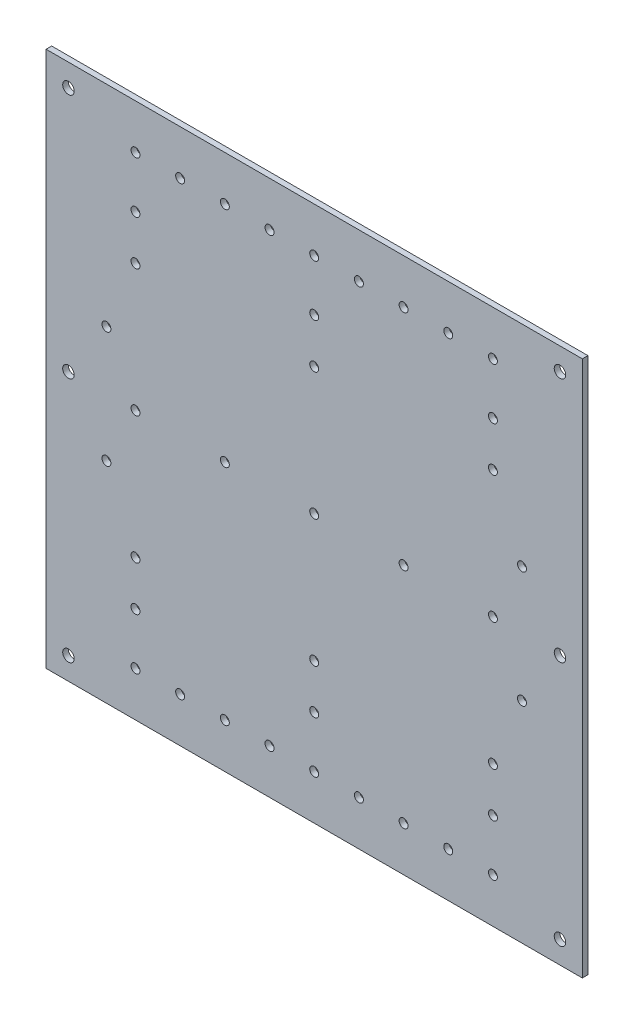
SolidWorks part; units mm, degrees
ref_plane "Front Plane" through (0, 0, 0) normal (0, 0, 1) x (1, 0, 0)
ref_plane "Top Plane" through (0, 0, 0) normal (0, 1, 0) x (1, 0, 0)
ref_plane "Right Plane" through (0, 0, 0) normal (1, 0, 0) x (0, 0, -1)
sketch "Sketch1" plane through (0, 0, 0) normal (0, 0, 1) x (1, 0, 0)
  line L0 (-152.4, 127) -> (-76.2, 127) construction
  line L1 (-152.4, 152.4) -> (152.4, 152.4)
  line L2 (-152.4, 152.4) -> (-152.4, -152.4)
  line L3 (-152.4, -152.4) -> (152.4, -152.4)
  line L4 (152.4, 152.4) -> (152.4, -152.4)
  line L5 (-76.2, 127) -> (-25.4, 127) construction
  line L6 (-25.4, 127) -> (25.4, 127) construction
  line L7 (25.4, 127) -> (76.2, 127) construction
  line L8 (76.2, 127) -> (152.4, 127) construction
  line L9 (-152.4, 0) -> (152.4, 0) construction
  line L10 (0, 152.4) -> (0, -152.4) construction
  line L11 (-118.11, 152.4) -> (-118.11, -152.4) construction
  line L12 (-152.4, -127) -> (152.4, -127) construction
  line L13 (127, 152.4) -> (127, -152.4) construction
  line L14 (-50.8, 152.4) -> (-50.8, -152.4) construction
  line L15 (50.8, 152.4) -> (50.8, -152.4) construction
  line L16 (-101.6, 152.4) -> (-101.6, -152.4) construction
  line L17 (-95.25, 66.04) -> (-57.15, 66.04) construction
  line L18 (-95.25, 66.04) -> (-95.25, -66.04) construction
  line L19 (-95.25, -66.04) -> (-57.15, -66.04) construction
  line L20 (-57.15, 66.04) -> (-57.15, -66.04) construction
  line L21 (-44.45, 66.04) -> (-6.35, 66.04) construction
  line L22 (-44.45, 66.04) -> (-44.45, -66.04) construction
  line L23 (-44.45, -66.04) -> (-6.35, -66.04) construction
  line L24 (-6.35, 66.04) -> (-6.35, -66.04) construction
  line L25 (6.35, 66.04) -> (44.45, 66.04) construction
  line L26 (6.35, 66.04) -> (6.35, -66.04) construction
  line L27 (6.35, -66.04) -> (44.45, -66.04) construction
  line L28 (44.45, 66.04) -> (44.45, -66.04) construction
  line L29 (57.15, 66.04) -> (95.25, 66.04) construction
  line L30 (57.15, 66.04) -> (57.15, -66.04) construction
  line L31 (57.15, -66.04) -> (95.25, -66.04) construction
  line L32 (95.25, 66.04) -> (95.25, -66.04) construction
  line L33 (101.6, 152.4) -> (101.6, -152.4) construction
  line L34 (-152.4, 120.65) -> (152.4, 120.65) construction
  line L35 (-101.6, 39.7057) -> (-95.25, 39.7057) construction
  line L36 (-57.15, 39.7057) -> (-50.8, 39.7057) construction
  line L37 (-76.2, 66.04) -> (-76.2, 0) construction
  line L38 (-76.2, 0) -> (-76.2, -66.04) construction
  line L39 (-152.4, 72.39) -> (152.4, 72.39) construction
  line L40 (-152.4, -72.39) -> (152.4, -72.39) construction
  line L41 (-76.2, 66.04) -> (-76.2, 72.39) construction
  line L42 (-95.25, -66.04) -> (-95.25, -72.39) construction
  line L43 (95.25, 39.7057) -> (101.6, 39.7057) construction
  line L44 (-95.25, 111.76) -> (-57.15, 111.76) construction
  line L45 (-57.15, 111.76) -> (-57.15, 118.4779) construction
  line L46 (-94.0266, 120.65) -> (-78.1749, 130.2582) construction
  line L47 (-95.25, 111.76) -> (-95.25, 118.4779) construction
  line L48 (-58.3734, 120.65) -> (-74.2251, 130.2582) construction
  line L49 (-107.3169, 130.81) -> (-83.1894, 130.81) construction
  line L50 (-6.35, 111.76) -> (-6.35, 118.4779) construction
  line L51 (-7.5734, 120.65) -> (-23.4251, 130.2582) construction
  line L52 (-43.2266, 120.65) -> (-27.3749, 130.2582) construction
  line L53 (-44.45, 111.76) -> (-44.45, 118.4779) construction
  line L54 (-6.35, 111.76) -> (-44.45, 111.76) construction
  line L55 (44.45, 111.76) -> (44.45, 118.4779) construction
  line L56 (43.2266, 120.65) -> (27.3749, 130.2582) construction
  line L57 (7.5734, 120.65) -> (23.4251, 130.2582) construction
  line L58 (6.35, 111.76) -> (6.35, 118.4779) construction
  line L59 (6.35, 111.76) -> (44.45, 111.76) construction
  line L60 (95.25, 111.76) -> (57.15, 111.76) construction
  line L61 (95.25, 111.76) -> (95.25, 118.4779) construction
  line L62 (94.0266, 120.65) -> (78.1749, 130.2582) construction
  line L63 (58.3734, 120.65) -> (74.2251, 130.2582) construction
  line L64 (57.15, 111.76) -> (57.15, 118.4779) construction
  line L65 (-95.25, -111.76) -> (-95.25, -118.4779) construction
  line L66 (-94.0266, -120.65) -> (-78.1749, -130.2582) construction
  line L67 (-58.3734, -120.65) -> (-74.2251, -130.2582) construction
  line L68 (-95.25, -111.76) -> (-57.15, -111.76) construction
  line L69 (-57.15, -111.76) -> (-57.15, -118.4779) construction
  line L70 (-44.45, -111.76) -> (-44.45, -118.4779) construction
  line L71 (-43.2266, -120.65) -> (-27.3749, -130.2582) construction
  line L72 (-6.35, -111.76) -> (-44.45, -111.76) construction
  line L73 (-7.5734, -120.65) -> (-23.4251, -130.2582) construction
  line L74 (-6.35, -111.76) -> (-6.35, -118.4779) construction
  line L75 (6.35, -111.76) -> (6.35, -118.4779) construction
  line L76 (7.5734, -120.65) -> (23.4251, -130.2582) construction
  line L77 (43.2266, -120.65) -> (27.3749, -130.2582) construction
  line L78 (6.35, -111.76) -> (44.45, -111.76) construction
  line L79 (44.45, -111.76) -> (44.45, -118.4779) construction
  line L80 (57.15, -111.76) -> (57.15, -118.4779) construction
  line L81 (58.3734, -120.65) -> (74.2251, -130.2582) construction
  line L82 (94.0266, -120.65) -> (78.1749, -130.2582) construction
  line L83 (95.25, -111.76) -> (57.15, -111.76) construction
  line L84 (95.25, -111.76) -> (95.25, -118.4779) construction
  line L85 (-152.4, 97.79) -> (152.4, 97.79) construction
  line L86 (-50.8, 39.7057) -> (-44.45, 39.7057) construction
  line L87 (-127, 152.4) -> (-127, -152.4) construction
  line L89 (-95.25, 101.6) -> (-92.3192, 101.6) construction
  line L90 (-95.25, 101.6) -> (-95.25, -101.6) construction
  line L96 (-90.8538, 101.6) -> (-90.8538, 68.58) construction
  line L97 (-89.3885, 101.6) -> (-89.3885, 68.58) construction
  line L98 (-92.3192, 101.6) -> (-92.3192, 68.58) construction
  line L99 (-83.5269, 101.6) -> (-83.5269, 68.58) construction
  line L100 (-86.4577, 101.6) -> (-86.4577, 68.58) construction
  line L101 (-89.3885, 101.6) -> (-86.4577, 101.6) construction
  line L102 (-77.6654, 101.6) -> (-77.6654, 68.58) construction
  line L103 (-80.5962, 101.6) -> (-80.5962, 68.58) construction
  line L104 (-83.5269, 101.6) -> (-80.5962, 101.6) construction
  line L105 (-71.8038, 101.6) -> (-71.8038, 68.58) construction
  line L106 (-74.7346, 101.6) -> (-74.7346, 68.58) construction
  line L107 (-77.6654, 101.6) -> (-74.7346, 101.6) construction
  line L108 (-65.9423, 101.6) -> (-65.9423, 68.58) construction
  line L109 (-68.8731, 101.6) -> (-68.8731, 68.58) construction
  line L110 (-71.8038, 101.6) -> (-68.8731, 101.6) construction
  line L111 (-60.0808, 101.6) -> (-60.0808, 68.58) construction
  line L112 (-63.0115, 101.6) -> (-63.0115, 68.58) construction
  line L113 (-65.9423, 101.6) -> (-63.0115, 101.6) construction
  line L114 (-57.15, -101.6) -> (-57.15, 101.6) construction
  line L115 (-60.0808, 101.6) -> (-57.15, 101.6) construction
  line L116 (-92.3192, 68.58) -> (-89.3885, 68.58) construction
  line L117 (-60.0808, -101.6) -> (-57.15, -101.6) construction
  line L118 (-60.0808, -101.6) -> (-60.0808, -68.58) construction
  line L119 (-63.0115, -101.6) -> (-63.0115, -68.58) construction
  line L120 (-65.9423, -101.6) -> (-65.9423, -68.58) construction
  line L121 (-65.9423, -101.6) -> (-63.0115, -101.6) construction
  line L122 (-68.8731, -101.6) -> (-68.8731, -68.58) construction
  line L123 (-71.8038, -101.6) -> (-68.8731, -101.6) construction
  line L124 (-71.8038, -101.6) -> (-71.8038, -68.58) construction
  line L125 (-74.7346, -101.6) -> (-74.7346, -68.58) construction
  line L126 (-77.6654, -101.6) -> (-74.7346, -101.6) construction
  line L127 (-77.6654, -101.6) -> (-77.6654, -68.58) construction
  line L128 (-80.5962, -101.6) -> (-80.5962, -68.58) construction
  line L129 (-83.5269, -101.6) -> (-80.5962, -101.6) construction
  line L130 (-83.5269, -101.6) -> (-83.5269, -68.58) construction
  line L131 (-86.4577, -101.6) -> (-86.4577, -68.58) construction
  line L132 (-89.3885, -101.6) -> (-86.4577, -101.6) construction
  line L133 (-89.3885, -101.6) -> (-89.3885, -68.58) construction
  line L134 (-92.3192, -101.6) -> (-92.3192, -68.58) construction
  line L135 (-95.25, -101.6) -> (-92.3192, -101.6) construction
  line L136 (-9.2808, 68.58) -> (-12.2115, 68.58) construction
  line L137 (6.35, 66.04) -> (44.45, 66.04) construction
  line L138 (-6.35, -66.04) -> (-6.35, -72.39) construction
  line L139 (-25.4, 66.04) -> (-25.4, 72.39) construction
  line L140 (-25.4, 0) -> (-25.4, -66.04) construction
  line L141 (-25.4, 66.04) -> (-25.4, 0) construction
  line L142 (-44.45, 66.04) -> (-44.45, -66.04) construction
  line L143 (-6.35, -66.04) -> (-44.45, -66.04) construction
  line L144 (-6.35, 66.04) -> (-6.35, -66.04) construction
  line L145 (-6.35, 66.04) -> (-44.45, 66.04) construction
  line L146 (-6.35, -101.6) -> (-9.2808, -101.6) construction
  line L147 (-9.2808, -101.6) -> (-9.2808, -68.58) construction
  line L148 (-12.2115, -101.6) -> (-12.2115, -68.58) construction
  line L149 (-12.2115, -101.6) -> (-15.1423, -101.6) construction
  line L150 (-15.1423, -101.6) -> (-15.1423, -68.58) construction
  line L151 (-18.0731, -101.6) -> (-18.0731, -68.58) construction
  line L152 (-18.0731, -101.6) -> (-21.0038, -101.6) construction
  line L153 (-21.0038, -101.6) -> (-21.0038, -68.58) construction
  line L154 (-23.9346, -101.6) -> (-23.9346, -68.58) construction
  line L155 (-23.9346, -101.6) -> (-26.8654, -101.6) construction
  line L156 (-26.8654, -101.6) -> (-26.8654, -68.58) construction
  line L157 (-29.7962, -101.6) -> (-29.7962, -68.58) construction
  line L158 (-29.7962, -101.6) -> (-32.7269, -101.6) construction
  line L159 (-32.7269, -101.6) -> (-32.7269, -68.58) construction
  line L160 (-35.6577, -101.6) -> (-38.5885, -101.6) construction
  line L161 (-35.6577, -101.6) -> (-35.6577, -68.58) construction
  line L162 (-38.5885, -101.6) -> (-38.5885, -68.58) construction
  line L163 (-41.5192, -101.6) -> (-41.5192, -68.58) construction
  line L164 (-41.5192, -101.6) -> (-44.45, -101.6) construction
  line L165 (-41.5192, 101.6) -> (-44.45, 101.6) construction
  line L166 (-44.45, -101.6) -> (-44.45, 101.6) construction
  line L167 (-35.6577, 101.6) -> (-38.5885, 101.6) construction
  line L168 (-38.5885, 101.6) -> (-38.5885, 68.58) construction
  line L169 (-41.5192, 101.6) -> (-41.5192, 68.58) construction
  line L170 (-29.7962, 101.6) -> (-32.7269, 101.6) construction
  line L171 (-32.7269, 101.6) -> (-32.7269, 68.58) construction
  line L172 (-35.6577, 101.6) -> (-35.6577, 68.58) construction
  line L173 (-23.9346, 101.6) -> (-26.8654, 101.6) construction
  line L174 (-26.8654, 101.6) -> (-26.8654, 68.58) construction
  line L175 (-29.7962, 101.6) -> (-29.7962, 68.58) construction
  line L176 (-18.0731, 101.6) -> (-21.0038, 101.6) construction
  line L177 (-21.0038, 101.6) -> (-21.0038, 68.58) construction
  line L178 (-23.9346, 101.6) -> (-23.9346, 68.58) construction
  line L179 (-12.2115, 101.6) -> (-15.1423, 101.6) construction
  line L180 (-15.1423, 101.6) -> (-15.1423, 68.58) construction
  line L181 (-18.0731, 101.6) -> (-18.0731, 68.58) construction
  line L182 (-9.2808, 101.6) -> (-9.2808, 68.58) construction
  line L183 (-12.2115, 101.6) -> (-12.2115, 68.58) construction
  line L184 (-6.35, 101.6) -> (-6.35, -101.6) construction
  line L185 (-6.35, 101.6) -> (-9.2808, 101.6) construction
  line L186 (6.35, 66.04) -> (6.35, -66.04) construction
  line L187 (6.35, -66.04) -> (44.45, -66.04) construction
  line L188 (44.45, 66.04) -> (44.45, -66.04) construction
  line L189 (25.4, 66.04) -> (25.4, 0) construction
  line L190 (25.4, 0) -> (25.4, -66.04) construction
  line L191 (25.4, 66.04) -> (25.4, 72.39) construction
  line L192 (6.35, -66.04) -> (6.35, -72.39) construction
  line L193 (9.2808, 68.58) -> (12.2115, 68.58) construction
  line L194 (6.35, 66.04) -> (6.35, -66.04) construction
  line L195 (44.45, -66.04) -> (6.35, -66.04) construction
  line L196 (44.45, 66.04) -> (44.45, -66.04) construction
  line L197 (44.45, 66.04) -> (6.35, 66.04) construction
  line L198 (6.35, 101.6) -> (9.2808, 101.6) construction
  line L199 (6.35, 101.6) -> (6.35, -101.6) construction
  line L200 (12.2115, 101.6) -> (12.2115, 68.58) construction
  line L201 (9.2808, 101.6) -> (9.2808, 68.58) construction
  line L202 (18.0731, 101.6) -> (18.0731, 68.58) construction
  line L203 (15.1423, 101.6) -> (15.1423, 68.58) construction
  line L204 (12.2115, 101.6) -> (15.1423, 101.6) construction
  line L205 (23.9346, 101.6) -> (23.9346, 68.58) construction
  line L206 (21.0038, 101.6) -> (21.0038, 68.58) construction
  line L207 (18.0731, 101.6) -> (21.0038, 101.6) construction
  line L208 (29.7962, 101.6) -> (29.7962, 68.58) construction
  line L209 (26.8654, 101.6) -> (26.8654, 68.58) construction
  line L210 (23.9346, 101.6) -> (26.8654, 101.6) construction
  line L211 (35.6577, 101.6) -> (35.6577, 68.58) construction
  line L212 (32.7269, 101.6) -> (32.7269, 68.58) construction
  line L213 (29.7962, 101.6) -> (32.7269, 101.6) construction
  line L214 (41.5192, 101.6) -> (41.5192, 68.58) construction
  line L215 (38.5885, 101.6) -> (38.5885, 68.58) construction
  line L216 (35.6577, 101.6) -> (38.5885, 101.6) construction
  line L217 (44.45, -101.6) -> (44.45, 101.6) construction
  line L218 (41.5192, 101.6) -> (44.45, 101.6) construction
  line L219 (41.5192, -101.6) -> (44.45, -101.6) construction
  line L220 (41.5192, -101.6) -> (41.5192, -68.58) construction
  line L221 (38.5885, -101.6) -> (38.5885, -68.58) construction
  line L222 (35.6577, -101.6) -> (35.6577, -68.58) construction
  line L223 (35.6577, -101.6) -> (38.5885, -101.6) construction
  line L224 (32.7269, -101.6) -> (32.7269, -68.58) construction
  line L225 (29.7962, -101.6) -> (32.7269, -101.6) construction
  line L226 (29.7962, -101.6) -> (29.7962, -68.58) construction
  line L227 (26.8654, -101.6) -> (26.8654, -68.58) construction
  line L228 (23.9346, -101.6) -> (26.8654, -101.6) construction
  line L229 (23.9346, -101.6) -> (23.9346, -68.58) construction
  line L230 (21.0038, -101.6) -> (21.0038, -68.58) construction
  line L231 (18.0731, -101.6) -> (21.0038, -101.6) construction
  line L232 (18.0731, -101.6) -> (18.0731, -68.58) construction
  line L233 (15.1423, -101.6) -> (15.1423, -68.58) construction
  line L234 (12.2115, -101.6) -> (15.1423, -101.6) construction
  line L235 (12.2115, -101.6) -> (12.2115, -68.58) construction
  line L236 (9.2808, -101.6) -> (9.2808, -68.58) construction
  line L237 (6.35, -101.6) -> (9.2808, -101.6) construction
  line L238 (57.15, 66.04) -> (95.25, 66.04) construction
  line L239 (57.15, 66.04) -> (57.15, -66.04) construction
  line L240 (57.15, -66.04) -> (95.25, -66.04) construction
  line L241 (95.25, 66.04) -> (95.25, -66.04) construction
  line L242 (92.3192, 68.58) -> (89.3885, 68.58) construction
  line L243 (95.25, -66.04) -> (95.25, -72.39) construction
  line L244 (76.2, 66.04) -> (76.2, 72.39) construction
  line L245 (76.2, 0) -> (76.2, -66.04) construction
  line L246 (76.2, 66.04) -> (76.2, 0) construction
  line L247 (57.15, 66.04) -> (57.15, -66.04) construction
  line L248 (95.25, -66.04) -> (57.15, -66.04) construction
  line L249 (95.25, 66.04) -> (95.25, -66.04) construction
  line L250 (95.25, 66.04) -> (57.15, 66.04) construction
  line L251 (57.15, 66.04) -> (57.15, -66.04) construction
  line L252 (95.25, -66.04) -> (57.15, -66.04) construction
  line L253 (95.25, 66.04) -> (95.25, -66.04) construction
  line L254 (95.25, 66.04) -> (57.15, 66.04) construction
  line L255 (95.25, -101.6) -> (92.3192, -101.6) construction
  line L256 (92.3192, -101.6) -> (92.3192, -68.58) construction
  line L257 (89.3885, -101.6) -> (89.3885, -68.58) construction
  line L258 (89.3885, -101.6) -> (86.4577, -101.6) construction
  line L259 (86.4577, -101.6) -> (86.4577, -68.58) construction
  line L260 (83.5269, -101.6) -> (83.5269, -68.58) construction
  line L261 (83.5269, -101.6) -> (80.5962, -101.6) construction
  line L262 (80.5962, -101.6) -> (80.5962, -68.58) construction
  line L263 (77.6654, -101.6) -> (77.6654, -68.58) construction
  line L264 (77.6654, -101.6) -> (74.7346, -101.6) construction
  line L265 (74.7346, -101.6) -> (74.7346, -68.58) construction
  line L266 (71.8038, -101.6) -> (71.8038, -68.58) construction
  line L267 (71.8038, -101.6) -> (68.8731, -101.6) construction
  line L268 (68.8731, -101.6) -> (68.8731, -68.58) construction
  line L269 (65.9423, -101.6) -> (63.0115, -101.6) construction
  line L270 (65.9423, -101.6) -> (65.9423, -68.58) construction
  line L271 (63.0115, -101.6) -> (63.0115, -68.58) construction
  line L272 (60.0808, -101.6) -> (60.0808, -68.58) construction
  line L273 (60.0808, -101.6) -> (57.15, -101.6) construction
  line L274 (60.0808, 101.6) -> (57.15, 101.6) construction
  line L275 (57.15, -101.6) -> (57.15, 101.6) construction
  line L276 (65.9423, 101.6) -> (63.0115, 101.6) construction
  line L277 (63.0115, 101.6) -> (63.0115, 68.58) construction
  line L278 (60.0808, 101.6) -> (60.0808, 68.58) construction
  line L279 (71.8038, 101.6) -> (68.8731, 101.6) construction
  line L280 (68.8731, 101.6) -> (68.8731, 68.58) construction
  line L281 (65.9423, 101.6) -> (65.9423, 68.58) construction
  line L282 (77.6654, 101.6) -> (74.7346, 101.6) construction
  line L283 (74.7346, 101.6) -> (74.7346, 68.58) construction
  line L284 (71.8038, 101.6) -> (71.8038, 68.58) construction
  line L285 (83.5269, 101.6) -> (80.5962, 101.6) construction
  line L286 (80.5962, 101.6) -> (80.5962, 68.58) construction
  line L287 (77.6654, 101.6) -> (77.6654, 68.58) construction
  line L288 (89.3885, 101.6) -> (86.4577, 101.6) construction
  line L289 (86.4577, 101.6) -> (86.4577, 68.58) construction
  line L290 (83.5269, 101.6) -> (83.5269, 68.58) construction
  line L291 (92.3192, 101.6) -> (92.3192, 68.58) construction
  line L292 (89.3885, 101.6) -> (89.3885, 68.58) construction
  line L293 (95.25, 101.6) -> (95.25, -101.6) construction
  line L294 (95.25, 101.6) -> (92.3192, 101.6) construction
  line L295 (-101.6, 39.7057) -> (-107.95, 39.7057) construction
  line L296 (-101.6, 78.74) -> (101.6, 78.74) construction
  line L297 (-107.95, 72.39) -> (-107.95, -72.39) construction
  line L298 (-101.6, -78.74) -> (101.6, -78.74) construction
  line L299 (107.95, 72.39) -> (107.95, -72.39) construction
  line L300 (-97.0611, 78.74) -> (-97.0611, 72.39) construction
  line L301 (-107.95, 22.225) -> (-120.65, 22.225) construction
  line L302 (-127, 15.875) -> (-127, -15.875) construction
  line L303 (-120.65, -22.225) -> (-107.95, -22.225) construction
  circle A0 centre (-76.2, 127) radius 2.5527
  circle A1 centre (-25.4, 127) radius 2.5527
  circle A2 centre (25.4, 127) radius 2.5527
  circle A3 centre (76.2, 127) radius 2.5527
  circle A4 centre (-101.6, 0) radius 2.54
  circle A5 centre (-50.8, 0) radius 2.54
  circle A6 centre (0, 0) radius 2.54
  circle A7 centre (101.6, 0) radius 2.54
  circle A8 centre (50.8, 0) radius 2.54
  circle A9 centre (-50.8, 127) radius 2.54
  circle A10 centre (0, 127) radius 2.54
  circle A11 centre (50.8, 127) radius 2.54
  circle A12 centre (-101.6, 72.39) radius 2.54
  circle A13 centre (0, 72.39) radius 2.54
  circle A14 centre (101.6, 72.39) radius 2.54
  circle A15 centre (-101.6, -72.39) radius 2.54
  circle A16 centre (0, -72.39) radius 2.54
  circle A17 centre (101.6, -72.39) radius 2.54
  arc A18 (-74.2251, 130.2582) -> (-78.1749, 130.2582) centre (-76.2, 127) ccw construction
  arc A19 (-57.15, 118.4779) -> (-58.3734, 120.65) centre (-59.69, 118.4779) ccw construction
  arc A20 (-95.25, 118.4779) -> (-94.0266, 120.65) centre (-92.71, 118.4779) cw construction
  arc A21 (-6.35, 118.4779) -> (-7.5734, 120.65) centre (-8.89, 118.4779) ccw construction
  arc A22 (-27.3749, 130.2582) -> (-23.4251, 130.2582) centre (-25.4, 127) cw construction
  arc A23 (-44.45, 118.4779) -> (-43.2266, 120.65) centre (-41.91, 118.4779) cw construction
  arc A24 (44.45, 118.4779) -> (43.2266, 120.65) centre (41.91, 118.4779) ccw construction
  arc A25 (27.3749, 130.2582) -> (23.4251, 130.2582) centre (25.4, 127) ccw construction
  arc A26 (6.35, 118.4779) -> (7.5734, 120.65) centre (8.89, 118.4779) cw construction
  arc A27 (95.25, 118.4779) -> (94.0266, 120.65) centre (92.71, 118.4779) ccw construction
  arc A28 (74.2251, 130.2582) -> (78.1749, 130.2582) centre (76.2, 127) cw construction
  arc A29 (57.15, 118.4779) -> (58.3734, 120.65) centre (59.69, 118.4779) cw construction
  circle A30 centre (-76.2, -127) radius 2.5527
  circle A31 centre (-25.4, -127) radius 2.5527
  circle A32 centre (25.4, -127) radius 2.5527
  circle A33 centre (76.2, -127) radius 2.5527
  arc A34 (-95.25, -118.4779) -> (-94.0266, -120.65) centre (-92.71, -118.4779) ccw construction
  arc A35 (-74.2251, -130.2582) -> (-78.1749, -130.2582) centre (-76.2, -127) cw construction
  arc A36 (-57.15, -118.4779) -> (-58.3734, -120.65) centre (-59.69, -118.4779) cw construction
  arc A37 (-44.45, -118.4779) -> (-43.2266, -120.65) centre (-41.91, -118.4779) ccw construction
  arc A38 (-27.3749, -130.2582) -> (-23.4251, -130.2582) centre (-25.4, -127) ccw construction
  arc A39 (-6.35, -118.4779) -> (-7.5734, -120.65) centre (-8.89, -118.4779) cw construction
  arc A40 (6.35, -118.4779) -> (7.5734, -120.65) centre (8.89, -118.4779) ccw construction
  arc A41 (27.3749, -130.2582) -> (23.4251, -130.2582) centre (25.4, -127) cw construction
  arc A42 (44.45, -118.4779) -> (43.2266, -120.65) centre (41.91, -118.4779) cw construction
  arc A43 (57.15, -118.4779) -> (58.3734, -120.65) centre (59.69, -118.4779) ccw construction
  arc A44 (74.2251, -130.2582) -> (78.1749, -130.2582) centre (76.2, -127) ccw construction
  arc A45 (95.25, -118.4779) -> (94.0266, -120.65) centre (92.71, -118.4779) cw construction
  circle A46 centre (50.8, -127) radius 2.54
  circle A47 centre (0, -127) radius 2.54
  circle A48 centre (-50.8, -127) radius 2.54
  circle A49 centre (-101.6, 97.79) radius 2.54
  circle A50 centre (0, 97.79) radius 2.54
  circle A51 centre (101.6, 97.79) radius 2.54
  circle A52 centre (101.6, 127) radius 2.54
  circle A53 centre (-101.6, 127) radius 2.54
  circle A54 centre (-118.11, 33.02) radius 2.54
  circle A56 centre (-101.6, -127) radius 2.54
  circle A57 centre (101.6, -127) radius 2.54
  circle A58 centre (101.6, -97.79) radius 2.54
  circle A59 centre (0, -97.79) radius 2.54
  circle A60 centre (-101.6, -97.79) radius 2.54
  circle A61 centre (-118.11, -33.02) radius 2.54
  circle A63 centre (-139.7, 139.7) radius 3.2639
  circle A64 centre (-139.7, 0) radius 3.2639
  circle A65 centre (-139.7, -139.7) radius 3.2639
  circle A66 centre (139.7, -139.7) radius 3.2639
  circle A67 centre (139.7, 0) radius 3.2639
  circle A68 centre (139.7, 139.7) radius 3.2639
  arc A70 (-92.3192, 68.58) -> (-89.3885, 68.58) centre (-90.8538, 68.58) ccw construction
  arc A71 (-86.4577, 68.58) -> (-83.5269, 68.58) centre (-84.9923, 68.58) ccw construction
  arc A72 (-80.5962, 68.58) -> (-77.6654, 68.58) centre (-79.1308, 68.58) ccw construction
  arc A73 (-74.7346, 68.58) -> (-71.8038, 68.58) centre (-73.2692, 68.58) ccw construction
  arc A74 (-68.8731, 68.58) -> (-65.9423, 68.58) centre (-67.4077, 68.58) ccw construction
  arc A75 (-63.0115, 68.58) -> (-60.0808, 68.58) centre (-61.5462, 68.58) ccw construction
  arc A76 (-63.0115, -68.58) -> (-60.0808, -68.58) centre (-61.5462, -68.58) cw construction
  arc A77 (-68.8731, -68.58) -> (-65.9423, -68.58) centre (-67.4077, -68.58) cw construction
  arc A78 (-74.7346, -68.58) -> (-71.8038, -68.58) centre (-73.2692, -68.58) cw construction
  arc A79 (-80.5962, -68.58) -> (-77.6654, -68.58) centre (-79.1308, -68.58) cw construction
  arc A80 (-86.4577, -68.58) -> (-83.5269, -68.58) centre (-84.9923, -68.58) cw construction
  arc A81 (-92.3192, -68.58) -> (-89.3885, -68.58) centre (-90.8538, -68.58) cw construction
  arc A82 (-9.2808, -68.58) -> (-12.2115, -68.58) centre (-10.7462, -68.58) ccw construction
  arc A83 (-15.1423, -68.58) -> (-18.0731, -68.58) centre (-16.6077, -68.58) ccw construction
  arc A84 (-21.0038, -68.58) -> (-23.9346, -68.58) centre (-22.4692, -68.58) ccw construction
  arc A85 (-26.8654, -68.58) -> (-29.7962, -68.58) centre (-28.3308, -68.58) ccw construction
  arc A86 (-32.7269, -68.58) -> (-35.6577, -68.58) centre (-34.1923, -68.58) ccw construction
  arc A87 (-38.5885, -68.58) -> (-41.5192, -68.58) centre (-40.0538, -68.58) ccw construction
  arc A88 (-38.5885, 68.58) -> (-41.5192, 68.58) centre (-40.0538, 68.58) cw construction
  arc A89 (-32.7269, 68.58) -> (-35.6577, 68.58) centre (-34.1923, 68.58) cw construction
  arc A90 (-26.8654, 68.58) -> (-29.7962, 68.58) centre (-28.3308, 68.58) cw construction
  arc A91 (-21.0038, 68.58) -> (-23.9346, 68.58) centre (-22.4692, 68.58) cw construction
  arc A92 (-15.1423, 68.58) -> (-18.0731, 68.58) centre (-16.6077, 68.58) cw construction
  arc A93 (-9.2808, 68.58) -> (-12.2115, 68.58) centre (-10.7462, 68.58) cw construction
  arc A94 (9.2808, 68.58) -> (12.2115, 68.58) centre (10.7462, 68.58) ccw construction
  arc A95 (15.1423, 68.58) -> (18.0731, 68.58) centre (16.6077, 68.58) ccw construction
  arc A96 (21.0038, 68.58) -> (23.9346, 68.58) centre (22.4692, 68.58) ccw construction
  arc A97 (26.8654, 68.58) -> (29.7962, 68.58) centre (28.3308, 68.58) ccw construction
  arc A98 (32.7269, 68.58) -> (35.6577, 68.58) centre (34.1923, 68.58) ccw construction
  arc A99 (38.5885, 68.58) -> (41.5192, 68.58) centre (40.0538, 68.58) ccw construction
  arc A100 (38.5885, -68.58) -> (41.5192, -68.58) centre (40.0538, -68.58) cw construction
  arc A101 (32.7269, -68.58) -> (35.6577, -68.58) centre (34.1923, -68.58) cw construction
  arc A102 (26.8654, -68.58) -> (29.7962, -68.58) centre (28.3308, -68.58) cw construction
  arc A103 (21.0038, -68.58) -> (23.9346, -68.58) centre (22.4692, -68.58) cw construction
  arc A104 (15.1423, -68.58) -> (18.0731, -68.58) centre (16.6077, -68.58) cw construction
  arc A105 (9.2808, -68.58) -> (12.2115, -68.58) centre (10.7462, -68.58) cw construction
  arc A106 (92.3192, -68.58) -> (89.3885, -68.58) centre (90.8538, -68.58) ccw construction
  arc A107 (86.4577, -68.58) -> (83.5269, -68.58) centre (84.9923, -68.58) ccw construction
  arc A108 (80.5962, -68.58) -> (77.6654, -68.58) centre (79.1308, -68.58) ccw construction
  arc A109 (74.7346, -68.58) -> (71.8038, -68.58) centre (73.2692, -68.58) ccw construction
  arc A110 (68.8731, -68.58) -> (65.9423, -68.58) centre (67.4077, -68.58) ccw construction
  arc A111 (63.0115, -68.58) -> (60.0808, -68.58) centre (61.5462, -68.58) ccw construction
  arc A112 (63.0115, 68.58) -> (60.0808, 68.58) centre (61.5462, 68.58) cw construction
  arc A113 (68.8731, 68.58) -> (65.9423, 68.58) centre (67.4077, 68.58) cw construction
  arc A114 (74.7346, 68.58) -> (71.8038, 68.58) centre (73.2692, 68.58) cw construction
  arc A115 (80.5962, 68.58) -> (77.6654, 68.58) centre (79.1308, 68.58) cw construction
  arc A116 (86.4577, 68.58) -> (83.5269, 68.58) centre (84.9923, 68.58) cw construction
  arc A117 (92.3192, 68.58) -> (89.3885, 68.58) centre (90.8538, 68.58) cw construction
  arc A118 (-101.6, 78.74) -> (-107.95, 72.39) centre (-101.6, 72.39) ccw construction
  arc A119 (-107.95, -72.39) -> (-101.6, -78.74) centre (-101.6, -72.39) ccw construction
  arc A120 (101.6, 78.74) -> (107.95, 72.39) centre (101.6, 72.39) cw construction
  arc A121 (101.6, -78.74) -> (107.95, -72.39) centre (101.6, -72.39) ccw construction
  arc A122 (-127, -15.875) -> (-120.65, -22.225) centre (-120.65, -15.875) ccw construction
  arc A123 (-120.65, 22.225) -> (-127, 15.875) centre (-120.65, 15.875) ccw construction
  circle A124 centre (118.11, -33.02) radius 2.54
  circle A125 centre (118.11, 33.02) radius 2.54
  point P10 (-76.2, 111.76)
  point P63 (50.8, 127)
  point P95 (-76.2, 66.04)
  point P97 (-25.4, 66.04)
  point P99 (25.4, 66.04)
  point P101 (76.2, 66.04)
  point P116 (-95.25, 0)
  point P118 (-44.45, 0)
  point P119 (6.35, 0)
  point P120 (57.15, 0)
  point P219 (-76.2, 33.02)
  point P259 (0, 78.74)
  point P260 (-107.95, 0)
  point P545 (-127, 0)
  point P548 (-127, -22.225)
  point P551 (-127, 22.225)
  dimension "D1" = 5.1054
  dimension "D7" = 5.08
  dimension "D11" = 7.62
  dimension "D13" = 2.54
  dimension "D19" = 6.5278
  dimension "D25" = 6.35
  dimension "D26" = 6.35
  dimension "D27" = 6.35
  dimension "D29" = 6.35
  dimension "D2" = 25.4
  dimension "D3" = 50.8
  dimension "D4" = 25.4
  dimension "D5" = 25.4
  dimension "D6" = 25.4
  dimension "D8" = 38.1
  dimension "D9" = 31.75
  dimension "D10" = 132.08
  dimension "D12" = 19.05
  dimension "D14" = 25.4
  dimension "D15" = 304.8
  dimension "D16" = 304.8
  dimension "D17" = 8.89
  dimension "D18" = 12.7
  dimension "D20" = 12.7
  dimension "D21" = 12.7
  dimension "D23" = 33.02
  dimension "D24" = 10.16
  dimension "D28" = 44.45
  dimension "D22" = 6
extrude "Boss-Extrude1" add sketch "Sketch1" along normal blind 3.175 contours L4 L1 L2 L3 A67 A125 A60 A58 A56 A124 A54 A53 A52 A51 A50 A49 A47 L84 A45 L82 A44 L81 A43 L80 L83 L74 A39 L73 A38 L71 A37 L70 L72 L64 A29
